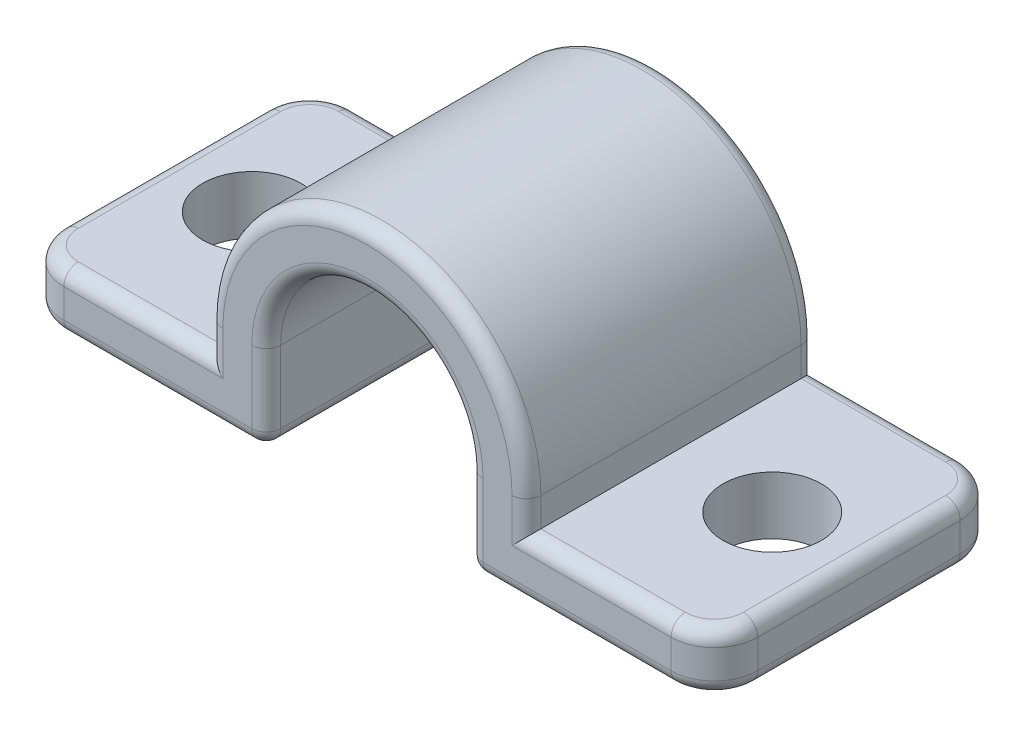
SolidWorks part; units mm, degrees
ref_plane "Front Plane" through (0, 0, 0) normal (0, 0, 1) x (1, 0, 0)
ref_plane "Top Plane" through (0, 0, 0) normal (0, 1, 0) x (1, 0, 0)
ref_plane "Right Plane" through (0, 0, 0) normal (1, 0, 0) x (0, 0, -1)
sketch "Sketch1" plane through (0, 0, 0) normal (0, 0, 1) x (1, 0, 0)
  line L0 (0, -1) -> (0, -3) construction
  line L1 (-12, -1) -> (12, -1)
  line L2 (-12, -1) -> (-12, -3)
  line L3 (-12, -3) -> (12, -3)
  line L4 (12, -1) -> (12, -3)
  line L5 (-11.2192, -3.5) -> (11.2192, -3.5) construction
  line L6 (-3.5, 0) -> (-3.5, -1)
  line L7 (3.5, 0) -> (3.5, -1)
  line L8 (5.5, 0) -> (5.5, -1)
  line L9 (-5.5, 0) -> (-5.5, -1)
  line L10 (-3.5, -1) -> (-3.5, -3)
  line L11 (3.5, -1) -> (3.5, -3)
  circle A0 centre (0, 0) radius 3.5
  circle A1 centre (0, 0) radius 5.5
  point P14 (0, -3.5)
  dimension "D1" = 7
  dimension "D2" = 2
  dimension "D3" = 2
  dimension "D4" = 1
  dimension "D5" = 24
extrude "Boss-Extrude1" add sketch "Sketch1" along normal blind 10 contours A1 L1 L6 A0 L7 | A1 L1 L8 | A1 L9 L1 | A1 L1 L2 L3 | L1 A1 L3 L10 | L3 A1 L1 L11 | A1 L3 L4 L1
sketch "Sketch2" plane through (0, -1, 0) normal (0, 1, 0) x (1, 0, 0)
  line L0 (-9, -5) -> (9, -5) construction
  line L1 (-12, 0) -> (12, 0)
  line L2 (0, 0) -> (0, -10) construction
  line L3 (-5.5, -10) -> (5.5, -10) construction
  point P1 (9, -5)
  point P11 (-9, -5)
  point P12 (0, -5)
  dimension "D1" = 18
  dimension "D2" = 5
hole_wizard "M3 Clearance Hole1" positions "Sketch2" profile "Sketch4" hole size "M3" standard "ANSI Metric"
sketch "Sketch4" plane through (9, -1, 5) normal (1, 0, 0) x (0, 0, 1)
  line L0 (0, 0) -> (0, 2)
  line L1 (0, 2) -> (1.7, 2)
  line L2 (1.7, 2) -> (1.7, 0)
  line L5 (1.7, 0) -> (0, 0)
  line L11 (0, -6.35) -> (0, 107.95) construction
  dimension "Thru Hole Dia." = 3.4
  dimension "Thru Hole Depth" = 2
sketch "Sketch5" plane through (0, 0, 0) normal (0, 0, -1) x (-1, 0, 0)
  line L0 (-5.5, -1) -> (-5.5, -3)
  line L1 (5.5, -1) -> (5.5, -3)
  line L10 (-5.5, -1) -> (-12, -1)
  line L11 (-12, -1) -> (-12, -3)
  line L12 (-12, -3) -> (-3.5, -3)
  line L13 (-3.5, -3) -> (-3.5, 0)
  line L14 (3.5, 0) -> (3.5, -3)
  line L15 (3.5, -3) -> (12, -3)
  line L16 (12, -3) -> (12, -1)
  line L17 (12, -1) -> (5.5, -1)
  line L18 (5.5, -1) -> (5.5, 0)
  line L19 (-5.5, 0) -> (-5.5, -1)
  line L20 (-5.5, -1) -> (-12, -1)
  line L21 (-12, -1) -> (-12, -3)
  line L22 (-12, -3) -> (-3.5, -3)
  line L23 (-3.5, -3) -> (-3.5, 0)
  line L24 (3.5, 0) -> (3.5, -3)
  line L25 (3.5, -3) -> (12, -3)
  line L26 (12, -3) -> (12, -1)
  line L27 (12, -1) -> (5.5, -1)
  line L28 (5.5, -1) -> (5.5, 0)
  line L29 (-5.5, 0) -> (-5.5, -1)
  arc A2 (3.5, 0) -> (-3.5, 0) centre (0, 0) ccw
  arc A3 (5.5, 0) -> (-5.5, 0) centre (0, 0) ccw
  arc A4 (3.5, 0) -> (-3.5, 0) centre (0, 0) ccw
  arc A5 (5.5, 0) -> (-5.5, 0) centre (0, 0) ccw
  dimension "D1" = 0
sketch "Sketch7" plane through (0, -1, 0) normal (0, 1, 0) x (1, 0, 0)
  line L0 (-12, -10) -> (-5.5, -10) construction
  line L1 (-9, -5) -> (9, -5) construction
  line L2 (-9, -5) -> (-9, -7) construction
  line L3 (-9, -7) -> (9, -7) construction
  line L4 (9, -5) -> (9, -7) construction
  point P1 (9, -7)
  point P2 (-9, -7)
  dimension "D1" = 18
  dimension "D2" = 3
fillet "Fillet1" radius 1.5 4 edges at (12, -2, 0) (12, -2, 10) (-12, -2, 0) (-12, -2, 10)
fillet "Fillet2" radius 0.5 34 edges at (3.5, -1.5, 0) (3.5, -1.5, 10) (-3.5, -1.5, 0) (-3.5, -1.5, 10) (-8, -1, 10) (-11.5607, -1, 9.5607) (-12, -1, 5) (-11.5607, -1, 0.4393) (8, -1, 10) (11.5607, -1, 9.5607) (12, -1, 5) (11.5607, -1, 0.4393) (5.5, -0.5, 0) (5.5, -0.5, 10) (-5.5, -0.5, 0) (-5.5, -0.5, 10) (0, 3.5, 0) (0, 3.5, 10) (-8, -1, 0) (8, -1, 0) (0, 5.5, 0) (0, 5.5, 10) (7, -3, 0) (11.5607, -3, 0.4393) (12, -3, 5) (11.5607, -3, 9.5607) (-7, -3, 10) (-7, -3, 0) (-11.5607, -3, 0.4393) (-12, -3, 5) (3.5, -3, 5) (7, -3, 10) (-3.5, -3, 5) (-11.5607, -3, 9.5607)
